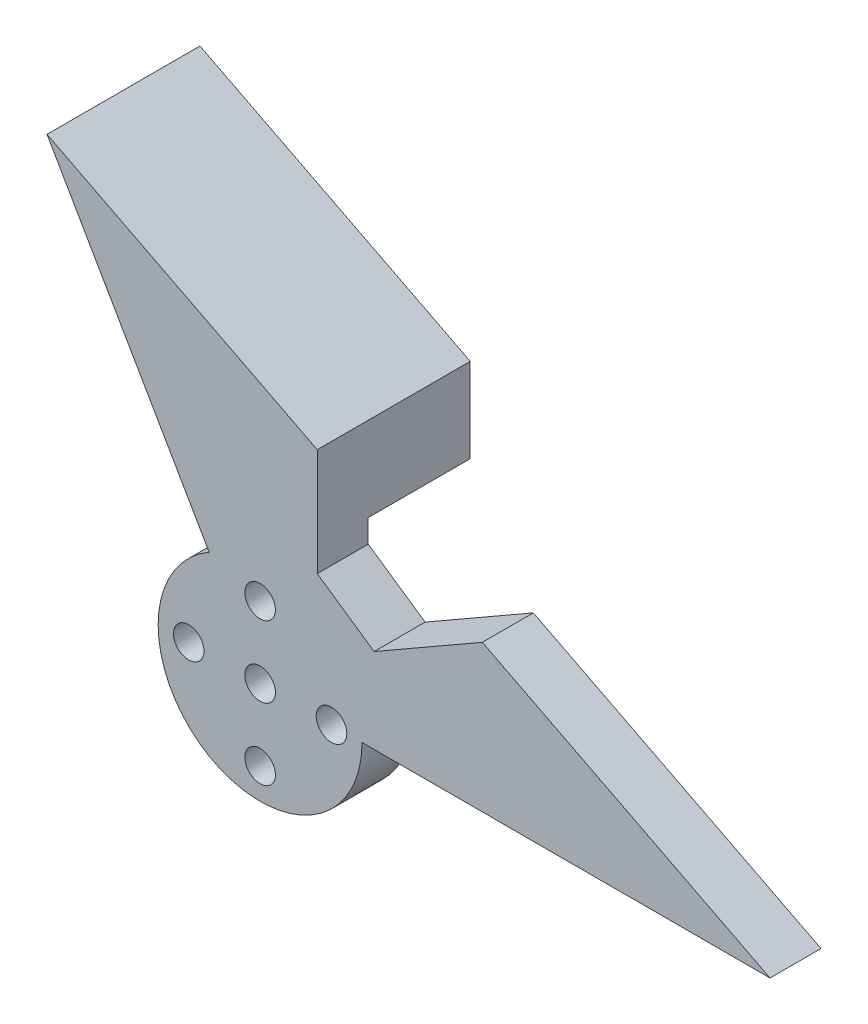
SolidWorks part; units mm, degrees
ref_plane "前视基准面" through (0, 0, 0) normal (0, 0, 1) x (1, 0, 0)
ref_plane "上视基准面" through (0, 0, 0) normal (0, 1, 0) x (1, 0, 0)
ref_plane "右视基准面" through (0, 0, 0) normal (1, 0, 0) x (0, 0, -1)
sketch "草图1" plane through (0, 0, 0) normal (0, 0, 1) x (1, 0, 0)
  circle A0 centre (0, 0) radius 10
  dimension "D1" = 20
extrude "凸台-拉伸1" add sketch "草图1" along normal blind 5
sketch "草图2" plane through (0, 0, 5) normal (0, 0, 1) x (1, 0, 0)
  line L0 (10, 0) -> (50, 0)
  line L1 (50, 0) -> (-20.8988, 36.1977)
  line L2 (-20.8988, 36.1977) -> (0, 0)
  line L3 (0, 0) -> (10, 0)
  circle A0 centre (0, 0) radius 10 construction
  dimension "D1" = 40
  dimension "D2" = 120
extrude "凸台-拉伸2" add sketch "草图2" against normal blind 5
sketch "草图3" plane through (0, 0, 5) normal (0, 0, 1) x (1, 0, 0)
  line L0 (5.6032, 25.2924) -> (5.6032, 12.1417)
  line L1 (5.6032, 12.1417) -> (11.1797, 8.313)
  line L2 (11.1797, 8.313) -> (24.6633, 16.0536)
  line L3 (24.6633, 16.0536) -> (5.6032, 25.2924)
extrude "切除-拉伸1" cut sketch "草图3" against normal blind 5
sketch "草图4" plane through (0, 0, 0) normal (0, 0, -1) x (-1, 0, 0)
  line L0 (-5.6032, 14.4034) -> (6.0643, 10.5036)
  line L7 (-5.6032, 12.1417) -> (-11.1797, 8.313)
  line L8 (-11.1797, 8.313) -> (-21.7888, 14.4034)
  line L9 (-21.7888, 14.4034) -> (-50, 0)
  line L10 (-50, 0) -> (-10, 0)
  line L11 (5, 8.6603) -> (20.8988, 36.1977)
  line L12 (20.8988, 36.1977) -> (-5.6032, 22.667)
  line L13 (-5.6032, 22.667) -> (-5.6032, 12.1417)
  line L14 (-5.6032, 12.1417) -> (-11.1797, 8.313)
  line L15 (-11.1797, 8.313) -> (-21.7888, 14.4034)
  line L16 (-21.7888, 14.4034) -> (-50, 0)
  line L17 (-50, 0) -> (-10, 0)
  line L18 (5, 8.6603) -> (20.8988, 36.1977)
  line L19 (20.8988, 36.1977) -> (-5.6032, 22.667)
  line L20 (-5.6032, 22.667) -> (-5.6032, 12.1417)
  arc A1 (-10, 0) -> (5, 8.6603) centre (0, 0) ccw
  arc A2 (-10, 0) -> (5, 8.6603) centre (0, 0) ccw
  line M14 (5, 8.6603) -> (20.8988, 36.1977)
  line M15 (20.8988, 36.1977) -> (-5.6032, 22.667)
  line M16 (-5.6032, 22.667) -> (-5.6032, 12.1417)
  dimension "D1" = 0
extrude "凸台-拉伸3" add sketch "草图4" along normal blind 10 contours L0 M16 M14 M15
sketch "草图5" plane through (0, 0, 5) normal (0, 0, 1) x (1, 0, 0)
  circle A0 centre (0, 0) radius 7
  circle A1 centre (0, 7) radius 1.5
  circle A2 centre (7, 0) radius 1.5
  circle A3 centre (0, -7) radius 1.5
  circle A4 centre (-7, 0) radius 1.5
  dimension "D1" = 14
  dimension "D2" = 3
  dimension "D3" = 3
  dimension "D4" = 3
  dimension "D5" = 3
extrude "切除-拉伸2" cut sketch "草图5" against normal blind 10 contours A0 A1 | A0 A1 | A2 | A3 | A4
sketch "草图6" plane through (0, 0, 5) normal (0, 0, 1) x (1, 0, 0)
  circle A0 centre (0, 0) radius 1.5
  dimension "D1" = 3
extrude "切除-拉伸3" cut sketch "草图6" against normal blind 10
